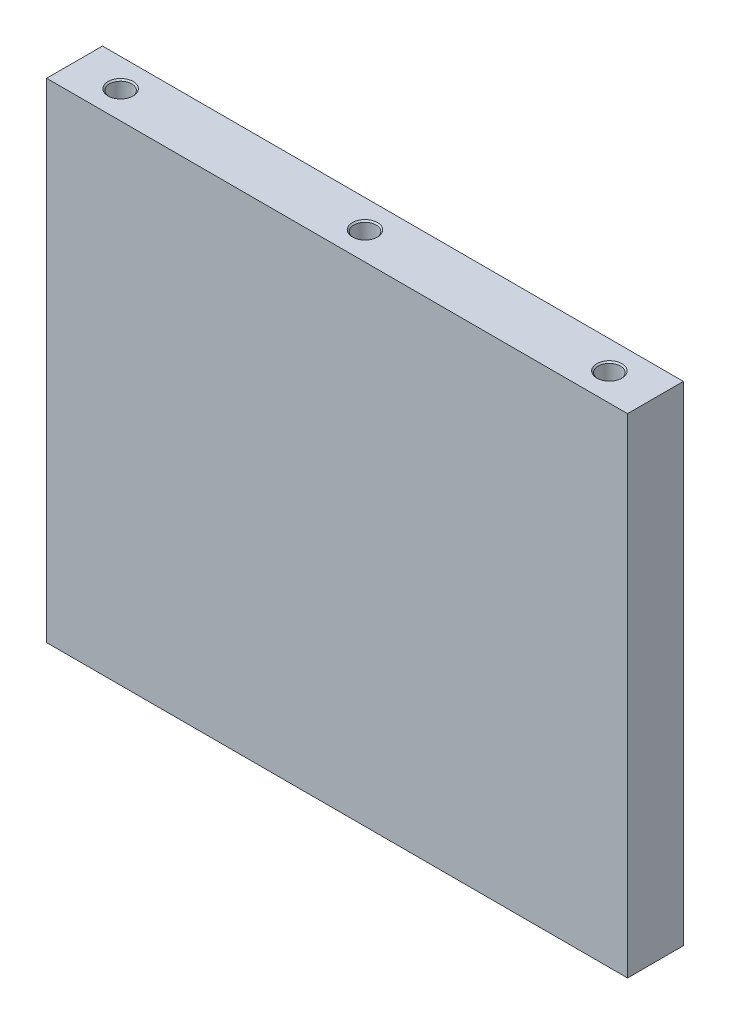
SolidWorks part; units mm, degrees
material "201 Annealed Stainless Steel (SS)"
ref_plane "Front Plane" through (0, 0, 0) normal (0, 0, 1) x (1, 0, 0)
ref_plane "Top Plane" through (0, 0, 0) normal (0, 1, 0) x (1, 0, 0)
ref_plane "Right Plane" through (0, 0, 0) normal (1, 0, 0) x (0, 0, -1)
sketch "Sketch1" plane through (0, 0, -58) normal (0, 1, 0) x (1, 0, 0)
  line L1 (-104, -68) -> (104, -68)
  line L2 (-104, -68) -> (-104, -48)
  line L3 (-104, -48) -> (104, -48)
  line L4 (104, -68) -> (104, -48)
  line L5 (0, -69) -> (0, -47) construction
  line L6 (-96.25, -58) -> (96.25, -58) construction
  point P5 (0, -68)
  point P8 (-104, -58)
  dimension "D1" = 208
  dimension "D2" = 20
extrude "Boss-Extrude1" add sketch "Sketch1" along normal blind 175
sketch "Sketch2" plane through (0, 175, 0) normal (0, 1, 0) x (1, 0, 0)
  line L0 (0, 0) -> (0, -51.17) construction
  circle A0 centre (0, 0) radius 4
  circle A1 centre (-87.5, 0) radius 4
  circle A2 centre (87.5, 0) radius 4
  dimension "D1" = 8
  dimension "D2" = 175
  dimension "D3" = 167
  dimension "D4" = 87.5
extrude "Cut-Extrude1" cut sketch "Sketch2" against normal blind 12
ref_plane "Plane1" through (0, 87.5, 0) normal (0, 1, 0) x (1, 0, 0)
sketch "Sketch3" plane through (0, 0, 0) normal (0, -1, 0) x (1, 0, 0)
  line L0 (0, 0) -> (0, 61.537) construction
  circle A0 centre (-55, 0) radius 4
  circle A1 centre (55, 0) radius 4
  circle A2 centre (0, 0) radius 4 construction
  dimension "D1" = 110
extrude "Cut-Extrude2" cut sketch "Sketch3" against normal blind 15
chamfer "Chamfer1" distance 0.5 angle 45 5 edges at (87.5, 175, -4) (0, 175, 4) (-87.5, 175, 4) (-55, 0, -4) (55, 0, 4)
